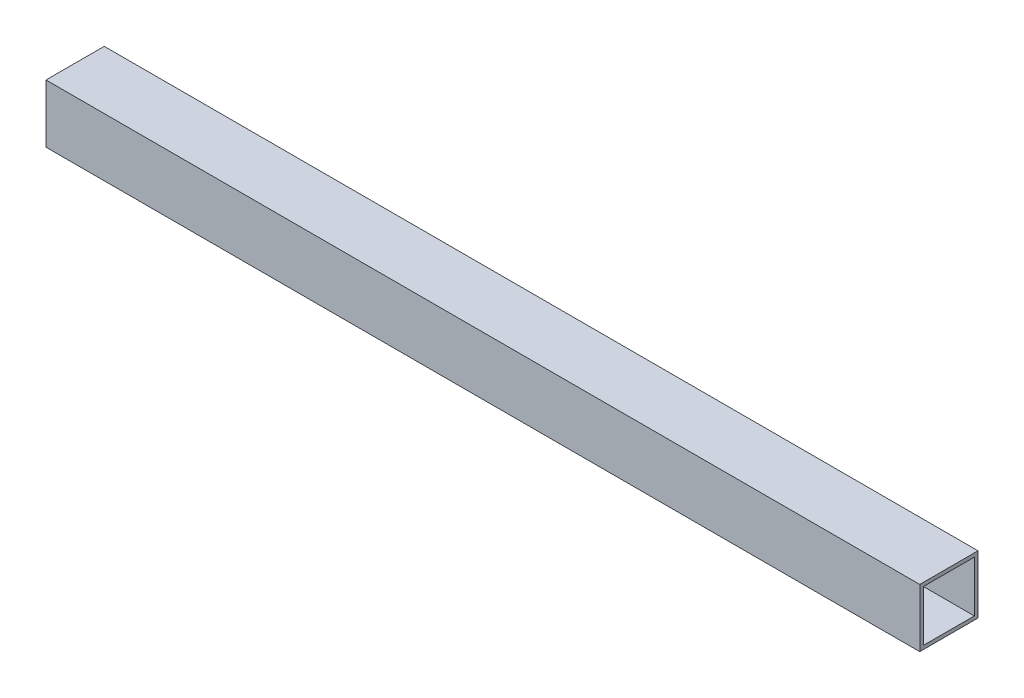
SolidWorks part; units mm, degrees
ref_plane "Front" through (0, 0, 0) normal (0, 0, 1) x (1, 0, 0)
ref_plane "Top" through (0, 0, 0) normal (0, 1, 0) x (1, 0, 0)
ref_plane "Right" through (0, 0, 0) normal (1, 0, 0) x (0, 0, -1)
sketch "Sketch1" plane through (0, 0, 0) normal (1, 0, 0) x (0, 0, -1)
  line L1 (-12.7, -12.7) -> (12.7, -12.7)
  line L2 (-12.7, -12.7) -> (-12.7, 12.7)
  line L3 (-12.7, 12.7) -> (12.7, 12.7)
  line L4 (12.7, -12.7) -> (12.7, 12.7)
  line L5 (-12.7, -12.7) -> (12.7, 12.7) construction
  line L6 (-12.7, 12.7) -> (12.7, -12.7) construction
  point P0 (0, 0)
  dimension "D1" = 25.4
extrude "Extrude-Thin1" add sketch "Sketch1" along normal blind 381 thin thin type one direction reverse wall 1.5875
